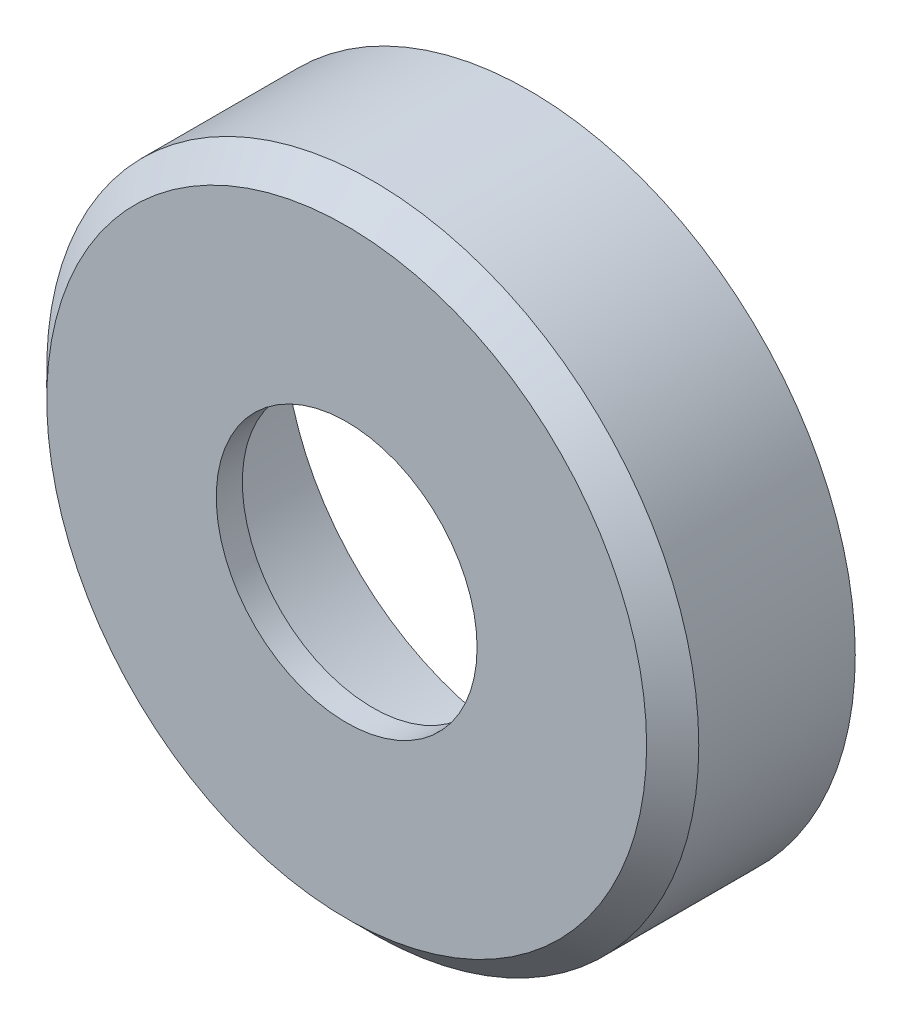
SolidWorks part; units mm, degrees
material "玻纤板"
ref_plane "前视基准面" through (0, 0, 0) normal (0, 0, 1) x (1, 0, 0)
ref_plane "上视基准面" through (0, 0, 0) normal (0, 1, 0) x (1, 0, 0)
ref_plane "右视基准面" through (0, 0, 0) normal (1, 0, 0) x (0, 0, -1)
sketch "草图1" plane through (0, 0, 0) normal (0, 0, 1) x (1, 0, 0)
  circle A0 centre (0, 0) radius 9.4
  circle A1 centre (0, 0) radius 12.5
  dimension "D1" = 18.8
  dimension "D2" = 25
extrude "凸台-拉伸1" add sketch "草图1" along normal blind 6
sketch "草图2" plane through (0, 0, 6) normal (0, 0, 1) x (1, 0, 0)
  circle A0 centre (0, 0) radius 12.5
  circle A1 centre (0, 0) radius 5
  circle A2 centre (0, 0) radius 12.5 construction
  dimension "D1" = 10
extrude "凸台-拉伸2" add sketch "草图2" along normal blind 1
chamfer "倒角1" distance 1 angle 45 1 edges at (12.5, 0, 7)
